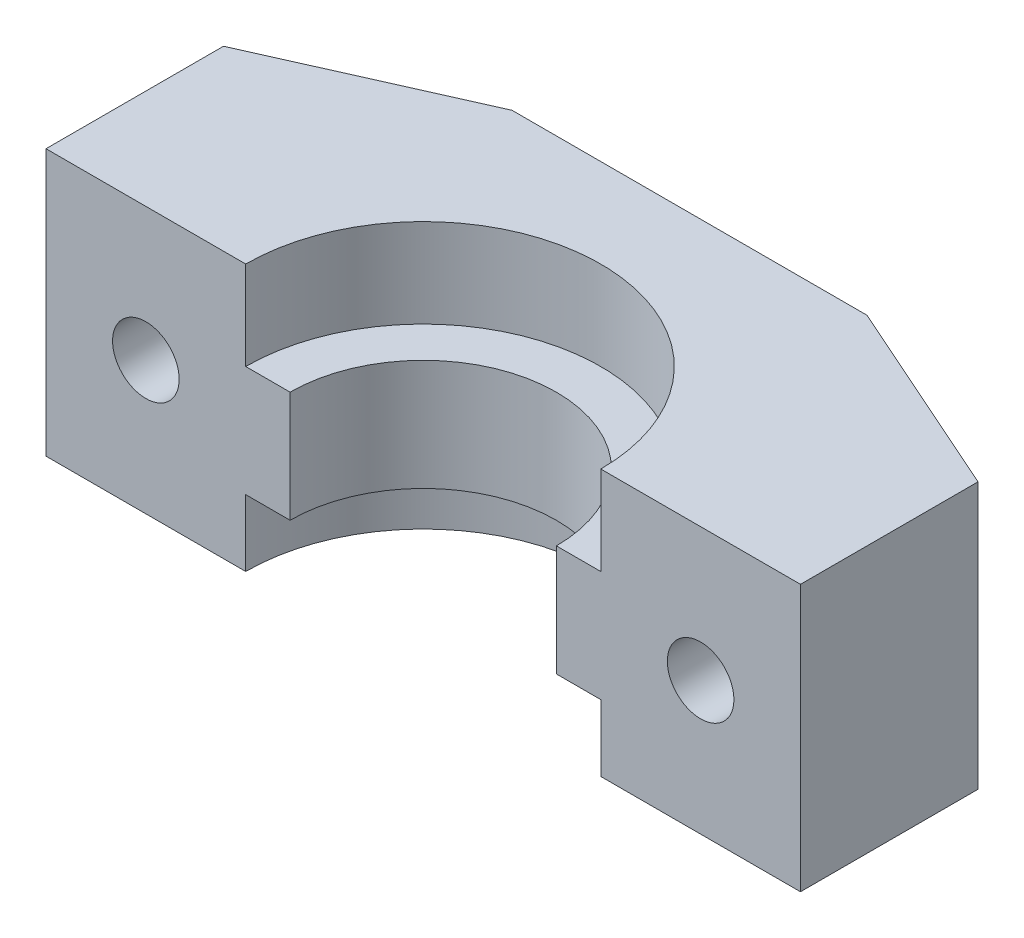
SolidWorks part; units mm, degrees
ref_plane "Спереди" through (0, 0, 0) normal (0, 0, 1) x (1, 0, 0)
ref_plane "Сверху" through (0, 0, 0) normal (0, 1, 0) x (1, 0, 0)
ref_plane "Справа" through (0, 0, 0) normal (1, 0, 0) x (0, 0, -1)
sketch "Эскиз2" plane through (0, 0, 0) normal (0, 1, 0) x (1, 0, 0)
  line L0 (0, 0) -> (0, 8)
  line L1 (34, 0) -> (34, 8)
  line L2 (9, 12) -> (25, 12)
  line L3 (0, 0) -> (11, 0)
  line L4 (34, 0) -> (23, 0)
  line L5 (9, 12) -> (0, 8)
  line L6 (25, 12) -> (34, 8)
  line L7 (17, 12) -> (17, 0) construction
  arc A0 (11, 0) -> (23, 0) centre (17, 0) cw
  point P12 (0, 0)
  point P13 (0, 0)
  point P14 (0, 0)
  dimension "D1" = 12
  dimension "D2" = 34
  dimension "D3" = 9
  dimension "D4" = 9
  dimension "D5" = 16
  dimension "D6" = 12
  dimension "D7" = 8
extrude "Бобышка-Вытянуть1" add sketch "Эскиз2" along normal blind 12
sketch "Эскиз3" plane through (0, 0, 0) normal (0, 0, 1) x (1, 0, 0)
  line L0 (0, 6) -> (34, 6) construction
  line L1 (0, 12) -> (0, 0) construction
  line L2 (34, 12) -> (34, 0) construction
  circle A0 centre (4.5, 6) radius 1.5
  circle A1 centre (29.5, 6) radius 1.5
  point P10 (0, 0)
  point P11 (0, 0)
  dimension "D1" = 3
  dimension "D2" = 3
  dimension "D3" = 4.5
  dimension "D4" = 4.5
extrude "Вырез-Вытянуть1" cut sketch "Эскиз3" against normal through all
sketch "Эскиз4" plane through (0, 0, 0) normal (0, 0, 1) x (1, 0, 0)
  circle A0 centre (4.5, 6) radius 3.5
  dimension "D1" = 7
extrude "Вырез-Вытянуть2" cut sketch "Эскиз4" against normal through all from offset 6 offset against normal yes
sketch "Эскиз5" plane through (0, 0, 0) normal (0, 0, 1) x (1, 0, 0)
  circle A0 centre (29.5, 6) radius 3.5
  dimension "D1" = 7
extrude "Вырез-Вытянуть4" cut sketch "Эскиз5" against normal through all from offset 6 offset against normal yes
sketch "Эскиз6" plane through (0, 12, 0) normal (0, 1, 0) x (1, 0, 0)
  line L0 (0, 0) -> (11, 0) construction
  line L1 (23, 0) -> (34, 0) construction
  arc A0 (9, 0) -> (25, 0) centre (17, 0) cw
  arc A1 (23, 0) -> (11, 0) centre (17, 0) ccw construction
  point P3 (0, 0)
  point P11 (17, 6)
  dimension "D1" = 16
extrude "Вырез-Вытянуть6" cut sketch "Эскиз6" against normal blind 4 and the other way through all flip side to cut
sketch "Эскиз7" plane through (0, 0, 0) normal (0, -1, 0) x (-1, 0, 0)
  line L0 (0, 0) -> (-11, 0) construction
  line L1 (-23, 0) -> (-34, 0) construction
  arc A0 (-9, 0) -> (-25, 0) centre (-17, 0) ccw
  arc A1 (-11, 0) -> (-23, 0) centre (-17, 0) ccw construction
  point P3 (0, 0)
  point P8 (0, 0)
  point P12 (-17, 6)
  dimension "D1" = 16
extrude "Вырез-Вытянуть7" cut sketch "Эскиз7" against normal blind 3 and the other way through all
